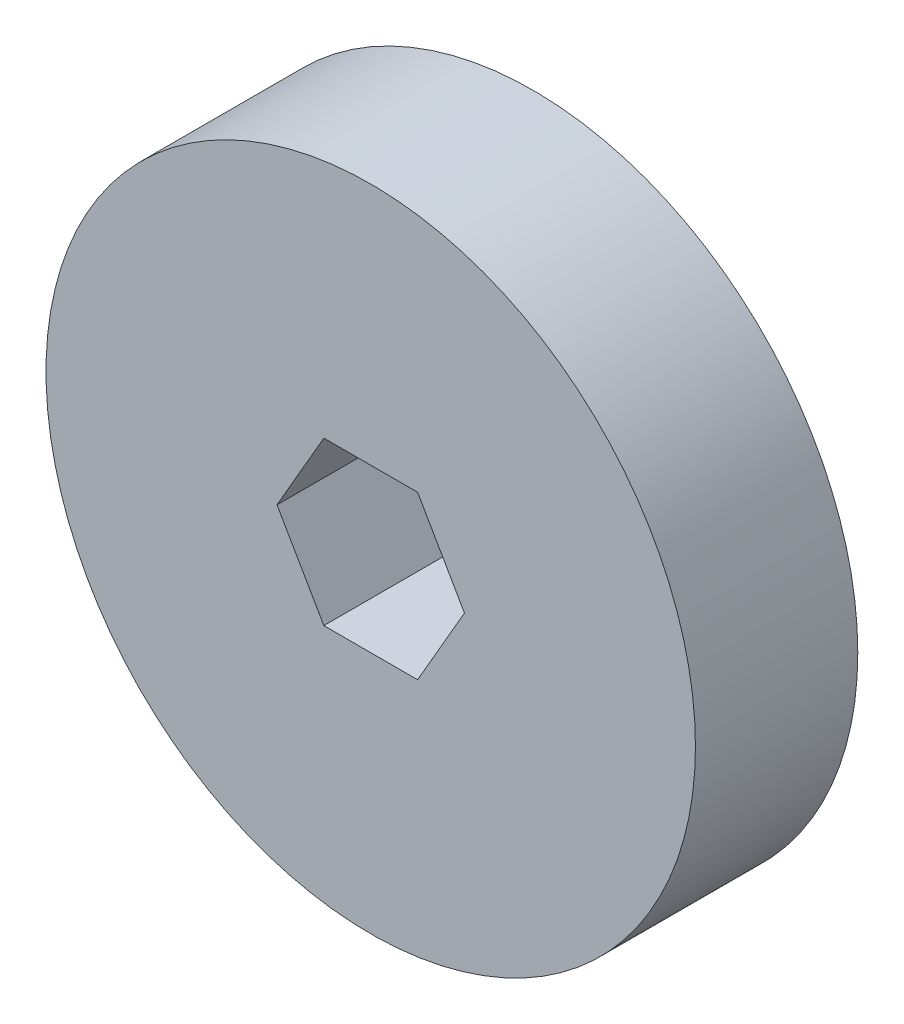
SolidWorks part; units mm, degrees
ref_plane "Front Plane" through (0, 0, 0) normal (0, 0, 1) x (1, 0, 0)
ref_plane "Top Plane" through (0, 0, 0) normal (0, 1, 0) x (1, 0, 0)
ref_plane "Right Plane" through (0, 0, 0) normal (1, 0, 0) x (0, 0, -1)
sketch "Sketch1" plane through (0, 0, 0) normal (0, 0, 1) x (1, 0, 0)
  circle A0 centre (0, 0) radius 25.4
  dimension "D1" = 50.8
extrude "Boss-Extrude1" add sketch "Sketch1" along normal blind 12.7
sketch "Sketch2" plane through (0, 0, 12.7) normal (0, 0, 1) x (1, 0, 0)
  line L1 (7.3323, 0) -> (3.6662, 6.35)
  line L2 (3.6662, 6.35) -> (-3.6662, 6.35)
  line L3 (-3.6662, 6.35) -> (-7.3323, 0)
  line L4 (-7.3323, 0) -> (-3.6662, -6.35)
  line L5 (-3.6662, -6.35) -> (3.6662, -6.35)
  line L6 (3.6662, -6.35) -> (7.3323, 0)
  circle A0 centre (0, 0) radius 6.35 construction
  dimension "D1" = 12.7
extrude "Cut-Extrude1" cut sketch "Sketch2" against normal through all both
